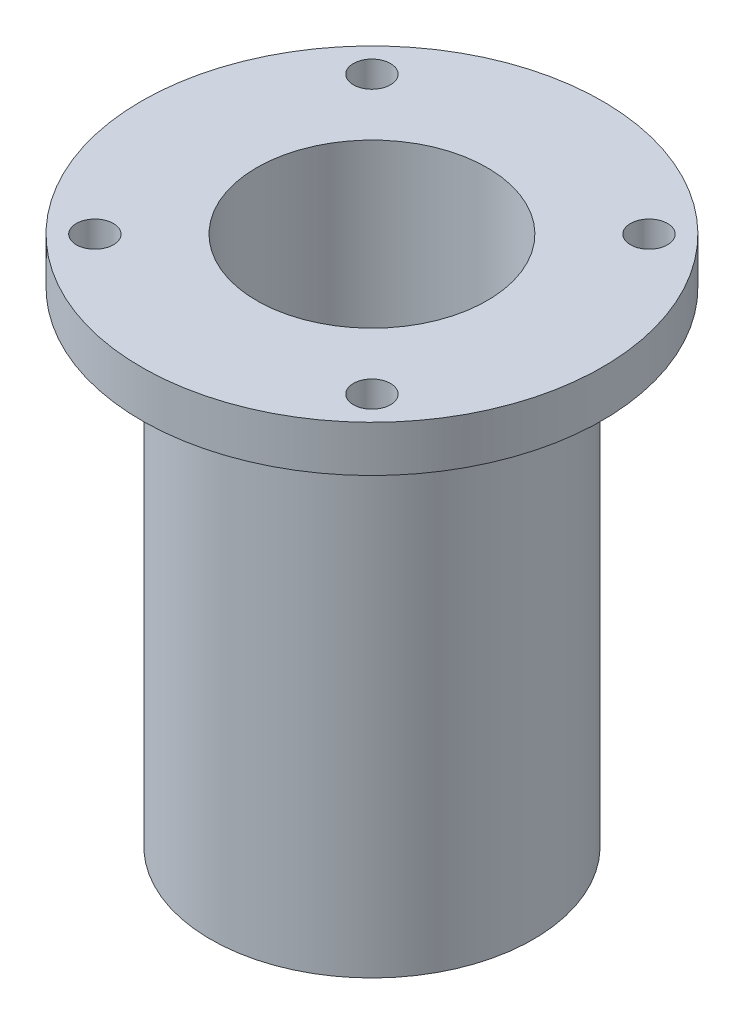
SolidWorks part; units mm, degrees
material "1023 Carbon Steel Sheet (SS)"
ref_plane "Front Plane" through (0, 0, 0) normal (0, 0, 1) x (1, 0, 0)
ref_plane "Top Plane" through (0, 0, 0) normal (0, 1, 0) x (1, 0, 0)
ref_plane "Right Plane" through (0, 0, 0) normal (1, 0, 0) x (0, 0, -1)
sketch "Sketch1" plane through (0, 0, 0) normal (0, 0, 1) x (1, 0, 0)
  line L0 (-31.75, 0) -> (-15.875, 0)
  line L1 (-15.875, 0) -> (-15.875, -63.5)
  line L2 (-15.875, -63.5) -> (0, -63.5)
  line L3 (0, -63.5) -> (0, -73.025)
  line L4 (0, -73.025) -> (-22.225, -73.025)
  line L5 (-22.225, -73.025) -> (-22.225, -6.35)
  line L6 (-22.225, -6.35) -> (-31.75, -6.35)
  line L7 (-31.75, -6.35) -> (-31.75, 0)
  line L8 (0, 0) -> (0, -73.025) construction
  point P10 (-31.75, -3.175)
  dimension "D1" = 63.5
  dimension "D2" = 31.75
  dimension "D3" = 9.525
  dimension "D4" = 6.35
  dimension "D5" = 31.75
  dimension "D6" = 6.35
revolve "Revolve1" add sketch "Sketch1" angle 360 about L8
hole_wizard "Pipe Tap Drill for 3/8 Tap1" positions "3DSketch1" profile "Sketch2" hole size "3/8" standard "ANSI Inch"
sketch3d "3DSketch1"
  circle A0 centre (0, -73.025, 0) radius 22.225 construction
  point P0 (0, -73.025, 0)
  point P5 (0, -50.8, 0)
sketch "Sketch2" plane through (0, -73.025, 0) normal (1, 0, 0) x (0, 0, -1)
  line L0 (0, 0) -> (0, 29.6886)
  line L1 (0, 29.6886) -> (7.1374, 25.4)
  line L2 (7.1374, 25.4) -> (7.1374, 0)
  line L5 (7.1374, 0) -> (0, 0)
  line L10 (0, 29.6886) -> (-7.1374, 25.4) construction
  line L11 (0, -6.35) -> (0, 107.95) construction
  dimension "Hole Dia." = 14.2748
  dimension "Hole Depth" = 25.4
  dimension "Drill Angle" = 118
hole_wizard "#10 Clearance Hole1" positions "3DSketch2" profile "Sketch3" hole size "#10" standard "ANSI Inch"
sketch3d "3DSketch2"
  line L0 (19.083, 0, -19.083) -> (0, 0, 0) construction
  line L2 (0, 0, 0) -> (31.75, 0, 0) construction
  line L4 (19.083, 0, -19.083) -> (22.4506, 0, -22.4506) construction
  circle A0 centre (0, 0, 0) radius 31.75 construction
  point P0 (19.083, 0, -19.083)
  point P11 (0, 31.75, 0)
  dimension "D1" = 45
  dimension "D2" = 4.7625
sketch "Sketch3" plane through (19.083, 0, -19.083) normal (1, 0, 0) x (0, 0, 1)
  line L0 (0, 0) -> (0, 26.9338)
  line L1 (0, 26.9338) -> (2.5527, 25.4)
  line L2 (2.5527, 25.4) -> (2.5527, 0)
  line L5 (2.5527, 0) -> (0, 0)
  line L10 (0, 26.9338) -> (-2.5527, 25.4) construction
  line L11 (0, -6.35) -> (0, 107.95) construction
  dimension "Hole Dia." = 5.1054
  dimension "Hole Depth" = 25.4
  dimension "Drill Angle" = 118
pattern_circular "CirPattern1" count 4 over 360 about axis through (0, 0, 0) along (0, 1, 0) of "#10 Clearance Hole1"
